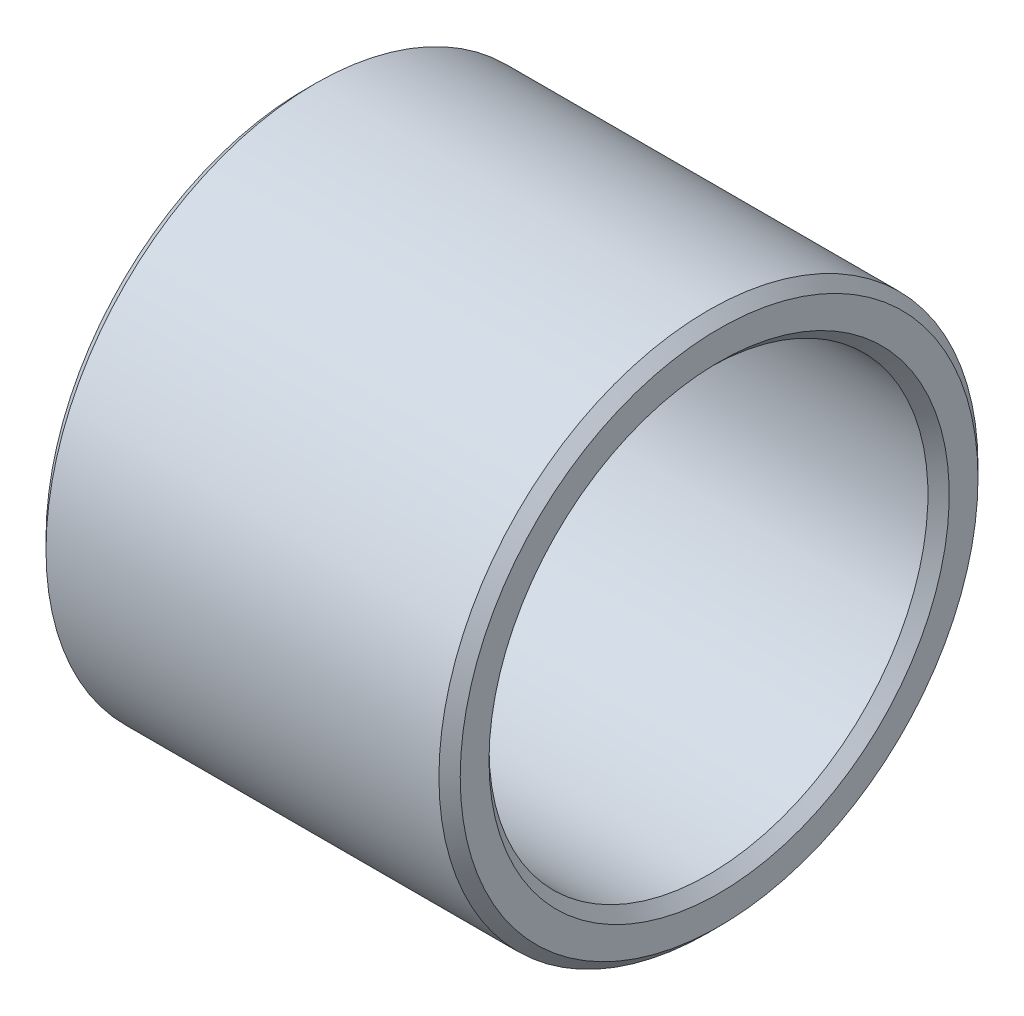
SolidWorks part; units mm, degrees
ref_plane "Plan de face" through (0, 0, 0) normal (0, 0, 1) x (1, 0, 0)
ref_plane "Plan de dessus" through (0, 0, 0) normal (0, 1, 0) x (1, 0, 0)
ref_plane "Plan de droite" through (0, 0, 0) normal (1, 0, 0) x (0, 0, -1)
sketch "Esquisse1" plane through (0, 0, 0) normal (0, 0, 1) x (1, 0, 0)
  line L0 (-10.6551, 0) -> (91.9494, 0) construction
  line L1 (0, 12.15) -> (0.5, 12.65)
  line L2 (0.5, 12.65) -> (18.94, 12.65)
  line L3 (0, 12.15) -> (0, 10.8)
  line L4 (0.5, 10.3) -> (18.94, 10.3)
  line L5 (19.44, 12.15) -> (19.44, 10.8)
  line L6 (0, 10.8) -> (0.5, 10.3)
  line L7 (18.94, 10.3) -> (19.44, 10.8)
  line L8 (18.94, 12.65) -> (19.44, 12.15)
  point P3 (0, 12.65)
  point P4 (19.44, 10.3)
  point P5 (0, 10.3)
  point P6 (19.44, 12.65)
  dimension "D1" = 19.44
  dimension "D2" = 20.6
  dimension "D3" = 25.3
  dimension "D6" = 0.5
  dimension "D7" = 0.5
  dimension "D8" = 0.5
  dimension "D9" = 0.5
revolve "Révolution1" add sketch "Esquisse1" angle 360 about L0
